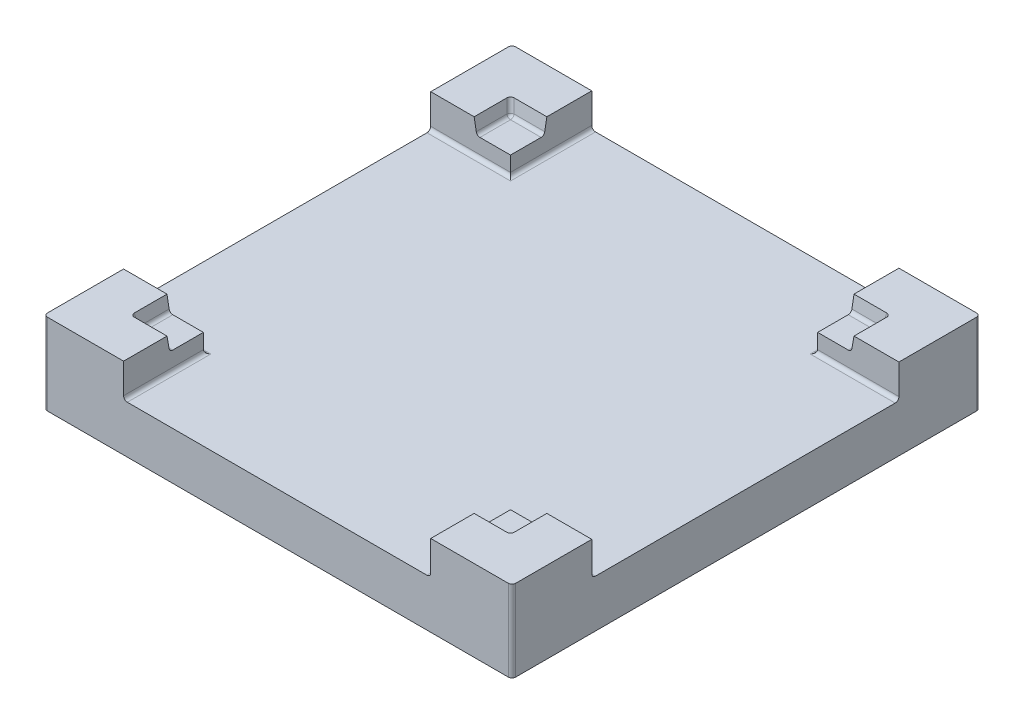
SolidWorks part; units mm, degrees
ref_plane "Front Plane" through (0, 0, 0) normal (0, 0, 1) x (1, 0, 0)
ref_plane "Top Plane" through (0, 0, 0) normal (0, 1, 0) x (1, 0, 0)
ref_plane "Right Plane" through (0, 0, 0) normal (1, 0, 0) x (0, 0, -1)
sketch "Sketch1" plane through (0, 0, 0) normal (0, 1, 0) x (1, 0, 0)
  line L1 (0, 0) -> (125, 0)
  line L2 (0, 0) -> (0, 125)
  line L3 (0, 125) -> (125, 125)
  line L4 (125, 0) -> (125, 125)
  dimension "D1" = 125
  dimension "D2" = 125
extrude "Boss-Extrude1" add sketch "Sketch1" along normal blind 21.7
sketch "Sketch2" plane through (0, 21.7, 0) normal (0, 1, 0) x (1, 0, 0)
  line L1 (12.3, 12.3) -> (112.3, 12.3)
  line L2 (12.3, 12.3) -> (12.3, 112.3)
  line L3 (12.3, 112.3) -> (112.3, 112.3)
  line L4 (112.3, 12.3) -> (112.3, 112.3)
  line L6 (125, 0) -> (125, 125) construction
  line L7 (125, 125) -> (0, 125) construction
  dimension "D1" = 100
  dimension "D2" = 100
  dimension "D3" = 12.7
  dimension "D4" = 12.7
extrude "Cut-Extrude1" cut sketch "Sketch2" against normal blind 9
fillet "Fillet2" radius 1 4 edges at (0, 10.85, -125) (0, 10.85, 0) (125, 10.85, 0) (125, 10.85, -125)
sketch "Sketch4" plane through (0, 21.7, 0) normal (0, 1, 0) x (1, 0, 0)
  line L0 (124, 125) -> (1, 125) construction
  line L1 (103.3, 125) -> (21.3, 125)
  line L2 (103.3, 125) -> (103.3, 112.3)
  line L3 (103.3, 112.3) -> (21.3, 112.3)
  line L4 (21.3, 125) -> (21.3, 112.3)
  line L5 (112.3, 112.3) -> (12.3, 112.3) construction
  line L6 (12.3, 112.3) -> (12.3, 12.3) construction
  line L7 (12.3, 103.3) -> (0, 103.3)
  line L8 (12.3, 103.3) -> (12.3, 21.3)
  line L9 (12.3, 21.3) -> (0, 21.3)
  line L10 (0, 103.3) -> (0, 21.3)
  line L11 (0, 124) -> (0, 1) construction
  line L12 (12.3, 12.3) -> (112.3, 12.3) construction
  line L13 (103.3, 12.3) -> (21.3, 12.3)
  line L14 (103.3, 12.3) -> (103.3, 0)
  line L15 (103.3, 0) -> (21.3, 0)
  line L16 (21.3, 12.3) -> (21.3, 0)
  line L17 (1, 0) -> (124, 0) construction
  line L18 (125, 1) -> (125, 124) construction
  line L19 (125, 103.3) -> (112.3, 103.3)
  line L20 (125, 103.3) -> (125, 21.3)
  line L21 (125, 21.3) -> (112.3, 21.3)
  line L22 (112.3, 103.3) -> (112.3, 21.3)
  line L23 (112.3, 12.3) -> (112.3, 112.3) construction
  point P32 (6.15, 21.3)
  dimension "D1" = 9
  dimension "D2" = 9
  dimension "D3" = 9
  dimension "D4" = 9
  dimension "D5" = 9
  dimension "D6" = 9
  dimension "D7" = 9
  dimension "D8" = 9
extrude "Cut-Extrude2" cut sketch "Sketch4" against normal blind 9
sketch "Sketch5" plane through (0, 12.7, 0) normal (0, 1, 0) x (1, 0, 0)
  line L1 (112.3, 12.3) -> (103.3, 12.3)
  line L2 (112.3, 12.3) -> (112.3, 21.3)
  line L3 (112.3, 21.3) -> (103.3, 21.3)
  line L4 (103.3, 12.3) -> (103.3, 21.3)
  line L5 (12.3, 12.3) -> (21.3, 12.3)
  line L6 (12.3, 12.3) -> (12.3, 21.3)
  line L7 (12.3, 21.3) -> (21.3, 21.3)
  line L8 (21.3, 12.3) -> (21.3, 21.3)
  line L9 (12.3, 112.3) -> (21.3, 112.3)
  line L10 (12.3, 112.3) -> (12.3, 103.3)
  line L11 (12.3, 103.3) -> (21.3, 103.3)
  line L12 (21.3, 112.3) -> (21.3, 103.3)
  line L13 (112.3, 112.3) -> (103.3, 112.3)
  line L14 (112.3, 112.3) -> (112.3, 103.3)
  line L15 (112.3, 103.3) -> (103.3, 103.3)
  line L16 (103.3, 112.3) -> (103.3, 103.3)
  dimension "D1" = 9
  dimension "D2" = 9
  dimension "D3" = 9
  dimension "D4" = 9
  dimension "D5" = 9
  dimension "D6" = 9
  dimension "D7" = 9
  dimension "D8" = 9
extrude "Boss-Extrude2" add sketch "Sketch5" along normal blind 5
draft "Draft1" type of draft neutral plane draft angle 10 faces to draft 2 face at (112.3, 19.7, -16.8) face at (107.8, 19.7, -12.3) neutral plane through (0, 17.7, 0) neutral plane normal (0, 1, 0) parameters "D1"=10
draft "Draft2" type of draft neutral plane draft angle 10 faces to draft 2 face at (12.3, 19.7, -16.8) face at (16.8, 19.7, -12.3) neutral plane through (0, 17.7, 0) neutral plane normal (0, 1, 0) parameters "D1"=10
draft "Draft3" type of draft neutral plane draft angle 10 faces to draft 2 face at (16.8, 19.7, -112.3) face at (12.3, 19.7, -107.8) neutral plane through (0, 17.7, 0) neutral plane normal (0, 1, 0) parameters "D1"=10
draft "Draft4" type of draft neutral plane draft angle 10 faces to draft 2 face at (112.3, 19.7, -107.8) face at (107.8, 19.7, -112.3) neutral plane through (0, 17.7, 0) neutral plane normal (0, 1, 0) parameters "D1"=10
fillet "Fillet3" radius 1 20 edges at (114.15, 12.7, -103.3) (103.3, 12.7, -114.15) (112.6527, 19.7, -112.6527) (107.8, 17.7, -112.3) (112.3, 17.7, -107.8) (114.15, 12.7, -21.3) (103.3, 12.7, -10.65) (112.3, 17.7, -16.8) (112.6527, 19.7, -11.9473) (107.8, 17.7, -12.3) (21.3, 12.7, -10.65) (10.65, 12.7, -21.3) (12.3, 17.7, -16.8) (11.9473, 19.7, -11.9473) (16.8, 17.7, -12.3) (21.3, 12.7, -114.15) (10.65, 12.7, -103.3) (11.9473, 19.7, -112.6527) (16.8, 17.7, -112.3) (12.3, 17.7, -107.8)
